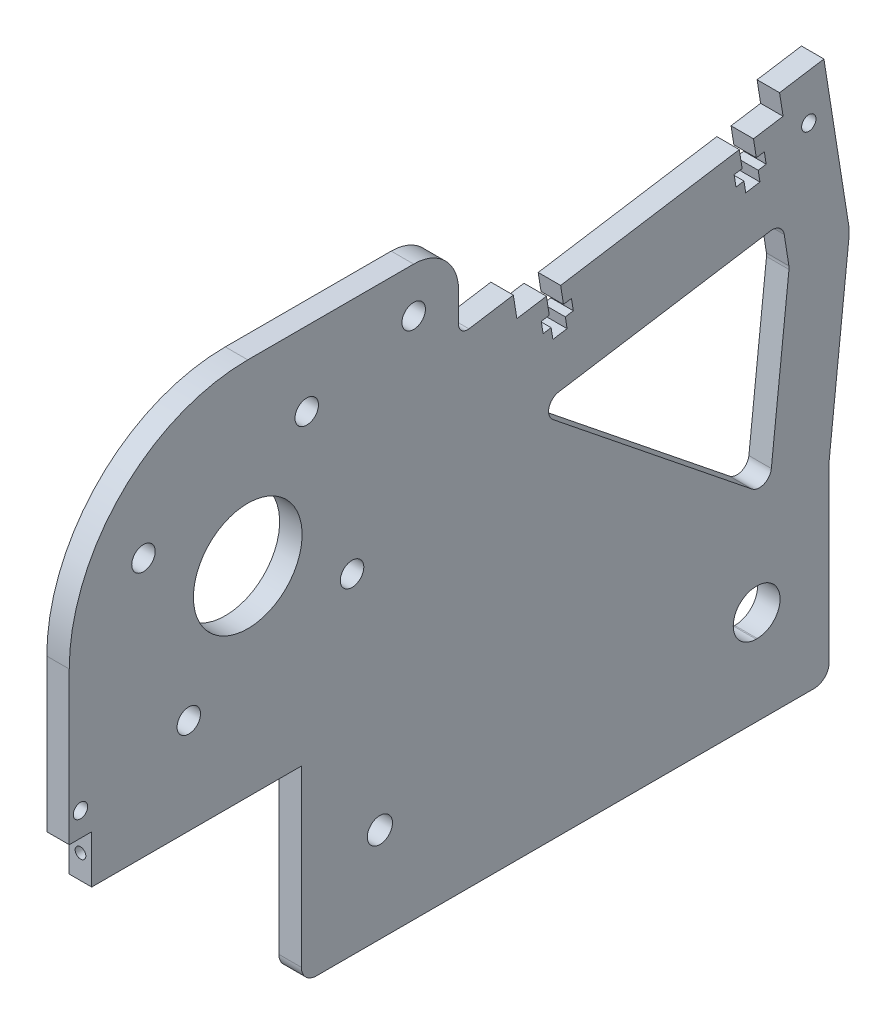
SolidWorks part; units mm, degrees
ref_plane "Front Plane" through (0, 0, 0) normal (0, 0, 1) x (1, 0, 0)
ref_plane "Top Plane" through (0, 0, 0) normal (0, 1, 0) x (1, 0, 0)
ref_plane "Right Plane" through (0, 0, 0) normal (1, 0, 0) x (0, 0, -1)
sketch "Sketch1" plane through (0, 0, 0) normal (1, 0, 0) x (0, 0, -1)
  line L0 (-28.1703, 0) -> (77.3828, 0)
  line L1 (80.5578, 3.175) -> (80.5578, 40.132)
  line L2 (-80.5578, 82.55) -> (-80.5578, 50.292)
  line L3 (4.1952, 102.6435) -> (13.6029, 104.1335)
  line L4 (-75.7953, 50.292) -> (-75.7953, 40.132)
  line L5 (-80.5578, 50.292) -> (-75.7953, 50.292)
  line L6 (65.3178, 20.066) -> (65.0638, 20.066) construction
  line L7 (-75.7953, 40.132) -> (-31.3453, 40.132)
  line L8 (1.9922, 110.875) -> (1.9922, 104.525)
  line L9 (-42.7078, 120.4) -> (-7.5328, 120.4)
  line L10 (-31.3453, 40.132) -> (-31.3453, 3.175)
  line L11 (-37.7935, 96.5728) -> (77.9184, 56.022) construction
  line L12 (-52.4128, 71.2982) -> (40.4331, -8.7847) construction
  line L13 (65.3178, 15.2273) -> (65.0638, 15.2273)
  line L14 (65.3178, 24.9047) -> (65.0638, 24.9047)
  line L15 (4.1952, 102.6435) -> (101.0919, 102.6435) construction
  line L16 (13.6029, 104.1335) -> (14.348, 99.4297)
  line L17 (14.348, 99.4297) -> (20.6198, 100.423)
  line L18 (70.7944, 108.3699) -> (70.0493, 113.0738)
  line L19 (70.0493, 113.0738) -> (79.4571, 114.5638)
  line L20 (79.4571, 114.5638) -> (84.7184, 81.3449)
  line L21 (84.7717, 79.1961) -> (80.5578, 40.132)
  line L22 (20.6198, 100.423) -> (21.2208, 96.6286)
  line L23 (21.2208, 96.6286) -> (19.5274, 96.3604)
  line L24 (19.5274, 96.3604) -> (19.9198, 93.883)
  line L25 (19.9198, 93.883) -> (21.6131, 94.1512)
  line L26 (26.317, 94.8962) -> (25.9246, 97.3736)
  line L27 (25.9246, 97.3736) -> (24.2312, 97.1054)
  line L28 (24.2312, 97.1054) -> (23.6303, 100.8998)
  line L29 (23.6303, 100.8998) -> (61.5121, 106.8997)
  line L30 (64.5225, 107.3765) -> (70.7944, 108.3699)
  line L31 (71.0359, 86.549) -> (72.0272, 80.29)
  line L38 (21.6131, 94.1512) -> (21.9857, 91.7993)
  line L39 (21.9857, 91.7993) -> (24.9961, 92.2761)
  line L40 (24.9961, 92.2761) -> (24.6236, 94.628)
  line L41 (24.6236, 94.628) -> (26.317, 94.8962)
  line L46 (61.5121, 106.8997) -> (62.113, 103.1053)
  line L47 (68.1298, 88.6604) -> (23.2189, 81.5472)
  line L48 (22.0267, 77.0573) -> (64.1879, 43.2308)
  line L49 (68.3027, 44.9396) -> (72.0438, 79.6202)
  line L50 (62.113, 103.1053) -> (60.4196, 102.8371)
  line L51 (60.4196, 102.8371) -> (60.812, 100.3597)
  line L52 (60.812, 100.3597) -> (62.5054, 100.6279)
  line L53 (67.2093, 101.3729) -> (66.8169, 103.8503)
  line L54 (66.8169, 103.8503) -> (65.1235, 103.5821)
  line L55 (65.1235, 103.5821) -> (64.5225, 107.3765)
  line L56 (62.5054, 100.6279) -> (62.8779, 98.276)
  line L57 (62.8779, 98.276) -> (65.8884, 98.7528)
  line L58 (65.8884, 98.7528) -> (65.5159, 101.1047)
  line L59 (65.5159, 101.1047) -> (67.2093, 101.3729)
  arc A0 (65.3178, 15.2273) -> (65.3178, 24.9047) centre (65.3178, 20.066) ccw
  circle A1 centre (-42.7078, 82.55) radius 31.5 construction
  circle A2 centre (65.3178, 20.066) radius 78.105 construction
  circle A3 centre (65.3178, 20.066) radius 38.1 construction
  circle A4 centre (-42.7078, 82.55) radius 14.859 construction
  arc A5 (-42.7078, 120.4) -> (-80.5578, 82.55) centre (-42.7078, 82.55) ccw
  arc A6 (-28.1703, 0) -> (-31.3453, 3.175) centre (-28.1703, 3.175) cw
  arc A7 (77.3828, 0) -> (80.5578, 3.175) centre (77.3828, 3.175) ccw
  circle A9 centre (-7.5328, 110.875) radius 6.35 construction
  circle A10 centre (-55.209, 60.4394) radius 2.4892
  circle A11 centre (-14.6922, 20.066) radius 2.667
  circle A12 centre (-20.5972, 70.0488) radius 2.4892
  circle A13 centre (-64.8184, 95.0512) radius 2.4892
  circle A14 centre (-30.2065, 104.6606) radius 2.4892
  circle A15 centre (-78.1765, 55.372) radius 1.524
  circle A16 centre (-42.7078, 82.55) radius 11.5228
  arc A17 (65.0638, 24.9047) -> (65.0638, 15.2273) centre (65.0638, 20.066) ccw
  arc A18 (-7.5328, 120.4) -> (1.9922, 110.875) centre (-7.5328, 110.875) cw
  circle A19 centre (-7.5328, 110.875) radius 2.4892
  arc A20 (4.1952, 102.6435) -> (1.9922, 104.525) centre (3.8972, 104.525) cw
  arc A21 (84.7184, 81.3449) -> (84.7717, 79.1961) centre (76.6695, 80.0701) cw
  circle A22 centre (76.2432, 104.411) radius 1.524
  arc A23 (72.0438, 79.6202) -> (72.0272, 80.29) centre (69.5185, 79.8927) ccw
  arc A24 (64.1879, 43.2308) -> (68.3027, 44.9396) centre (65.7774, 45.212) ccw
  arc A25 (23.2189, 81.5472) -> (22.0267, 77.0573) centre (23.6162, 79.0385) ccw
  arc A26 (68.1298, 88.6604) -> (71.0359, 86.549) centre (68.5271, 86.1517) cw
  point P39 (65.1908, 20.066)
  dimension "D4" = 9.6774
  dimension "D7" = 29.718
  dimension "D8" = 63
  dimension "D9" = 6.35
  dimension "D12" = 3.175
  dimension "D13" = 4.7625
  dimension "D14" = 76.2
  dimension "D15" = 156.21
  dimension "D18" = 5.334
  dimension "D19" = 9.525
  dimension "D20" = 9.525
  dimension "D23" = 3.048
  dimension "D27" = 73.025
  dimension "D28" = 12.7
  dimension "D29" = 4.9784
  dimension "D31" = 1.905
  dimension "D33" = 3.048
  dimension "D42" = 2.54
  dimension "D43" = 2.54
  dimension "D44" = 86.36
  dimension "D48" = 3.048
  dimension "D49" = 9.525
  dimension "D2" = 40.132
  dimension "D3" = 20.066
  dimension "D5" = 15.24
  dimension "D6" = 44.45
  dimension "D10" = 161.1156
  dimension "D11" = 95.25
  dimension "D17" = 9
  dimension "D21" = 4.7625
  dimension "D22" = 10.16
  dimension "D24" = 5.08
  dimension "D25" = 2.3813
  dimension "D26" = 0.254
  dimension "D16" = 76.2
  dimension "D30" = 9.525
  dimension "D34" = 19.05
  dimension "D35" = 8.7312
  dimension "D36" = 2.5083
  dimension "D37" = 6.477
  dimension "D38" = 6.35
  dimension "D40" = 12.7
  dimension "D45" = 6.35
  dimension "D46" = 6.35
  dimension "D47" = 4.7625
  dimension "D50" = 5.08
  dimension "D39" = 2
extrude "Boss-Extrude1" add sketch "Sketch1" along normal blind 4.7625
sketch "Sketch2" plane through (0, 0, 75.7953) normal (0, 0, 1) x (1, 0, 0)
  line L0 (4.7625, 50.292) -> (4.7625, 40.132) construction
  line L1 (4.7625, 40.132) -> (0, 40.132) construction
  circle A0 centre (2.3813, 45.212) radius 1.1303
  point P4 (4.7625, 45.212)
  point P7 (2.3813, 40.132)
  dimension "D1" = 2.2606
extrude "Cut-Extrude1" cut sketch "Sketch2" against normal blind 6.35
